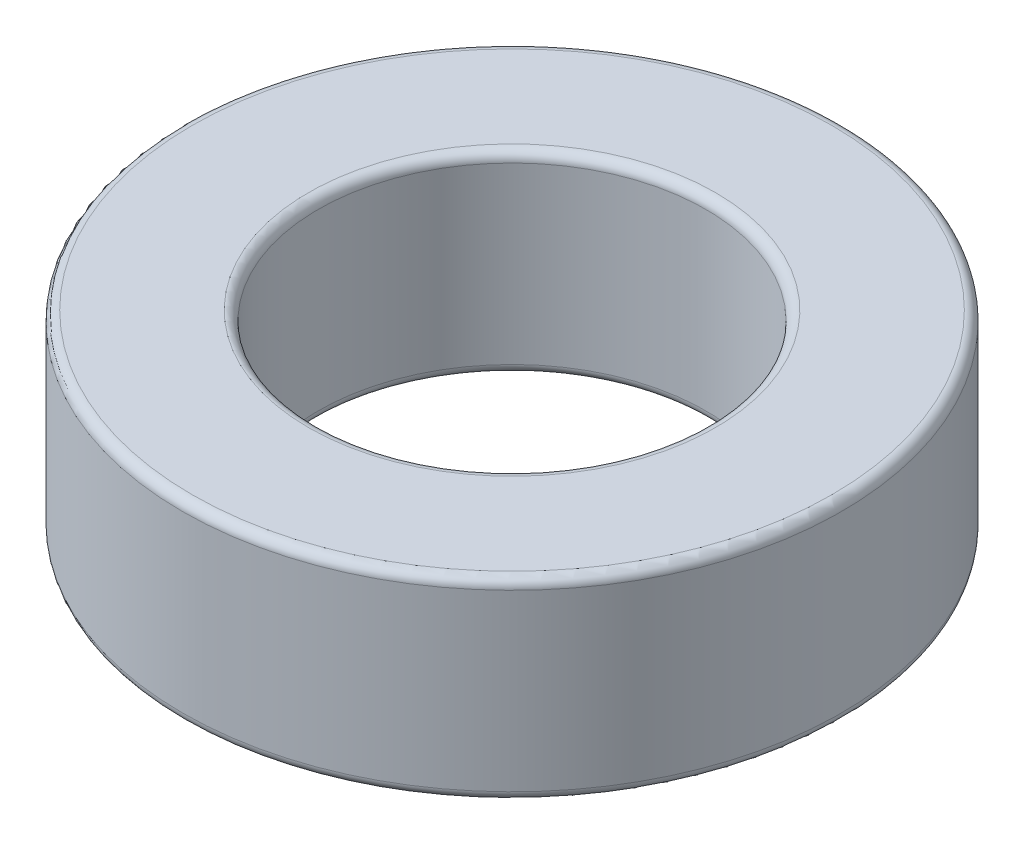
SolidWorks part; units mm, degrees
ref_plane "前视基准面" through (0, 0, 0) normal (0, 0, 1) x (1, 0, 0)
ref_plane "上视基准面" through (0, 0, 0) normal (0, 1, 0) x (1, 0, 0)
ref_plane "右视基准面" through (0, 0, 0) normal (1, 0, 0) x (0, 0, -1)
other "Configuration Table"
sketch "草图1" plane through (0, 0, 0) normal (0, 1, 0) x (1, 0, 0)
  circle A0 centre (0, 0) radius 8.5
  circle A1 centre (0, 0) radius 5
  dimension "D1" = 10
  dimension "D2" = 17
extrude "凸台-拉伸1" add sketch "草图1" along normal blind 5
fillet "圆角1" radius 0.25 4 edges at (0, 0, 5) (0, 5, 5) (0, 0, 8.5) (0, 5, 8.5)
